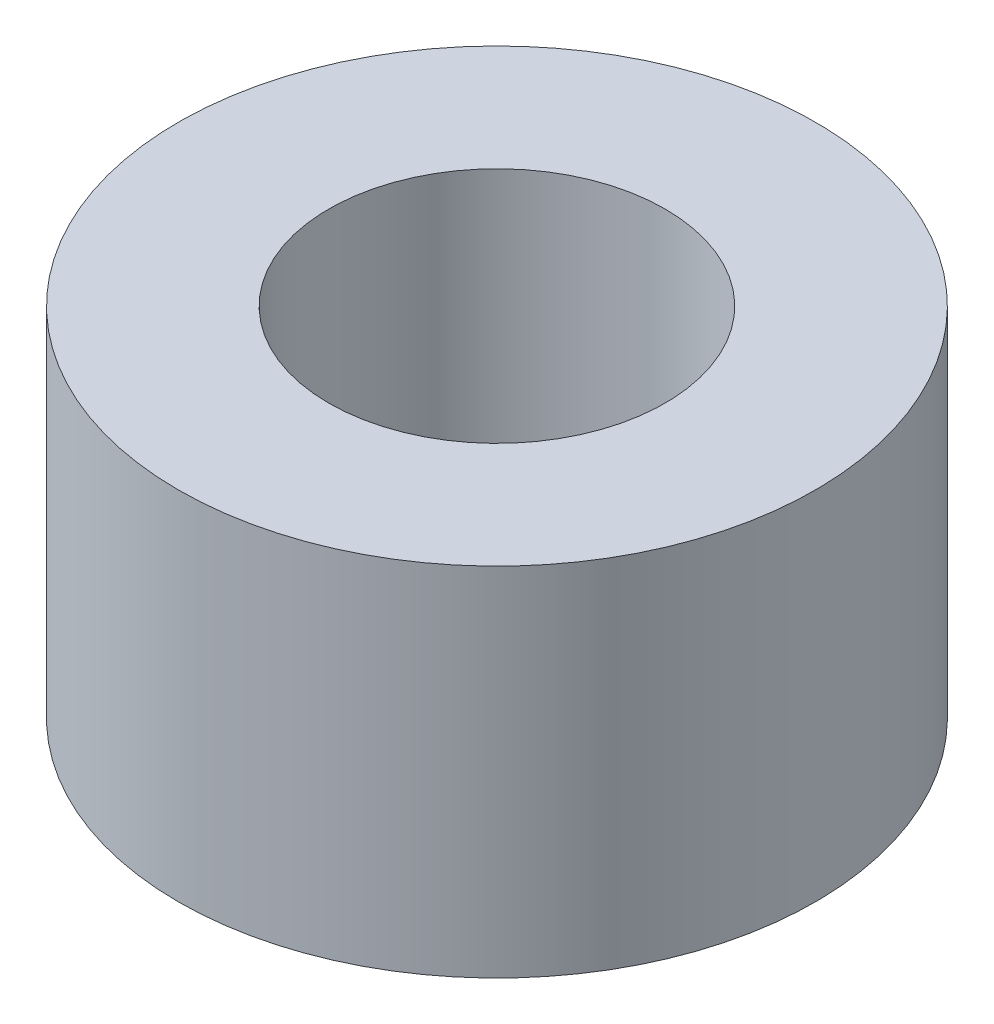
SolidWorks part; units mm, degrees
ref_plane "Front Plane" through (0, 0, 0) normal (0, 0, 1) x (1, 0, 0)
ref_plane "Top Plane" through (0, 0, 0) normal (0, 1, 0) x (1, 0, 0)
ref_plane "Right Plane" through (0, 0, 0) normal (1, 0, 0) x (0, 0, -1)
sketch "Sketch1" plane through (0, 0, 0) normal (0, 1, 0) x (1, 0, 0)
  circle A0 centre (0, 0) radius 3.3
  circle A1 centre (0, 0) radius 6.25
  dimension "D1" = 6.6
  dimension "D2" = 12.5
extrude "Boss-Extrude1" add sketch "Sketch1" along normal blind 7
